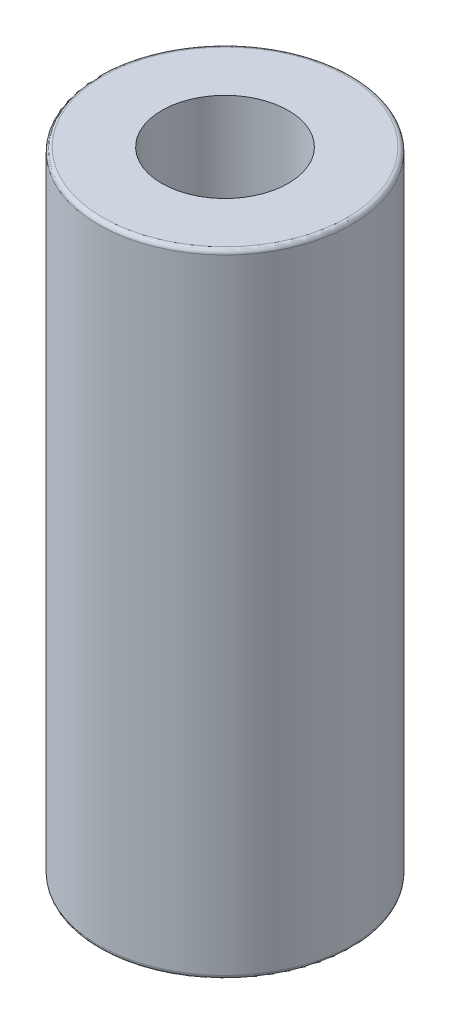
SolidWorks part; units mm, degrees
ref_plane "正面" through (0, 0, 0) normal (0, 0, 1) x (1, 0, 0)
ref_plane "平面" through (0, 0, 0) normal (0, 1, 0) x (1, 0, 0)
ref_plane "右側面" through (0, 0, 0) normal (1, 0, 0) x (0, 0, -1)
sketch "ｽｹｯﾁ1" plane through (0, 0, 0) normal (0, 1, 0) x (1, 0, 0)
  circle A0 centre (0, 0) radius 1.5
  circle A1 centre (0, 0) radius 3
  dimension "D1" = 3
  dimension "D2" = 6
extrude "ﾎﾞｽ - 押し出し1" add sketch "ｽｹｯﾁ1" along normal blind 15
fillet "ﾌｨﾚｯﾄ1" radius 0.1 2 edges at (0, 0, 3) (0, 15, 3)
